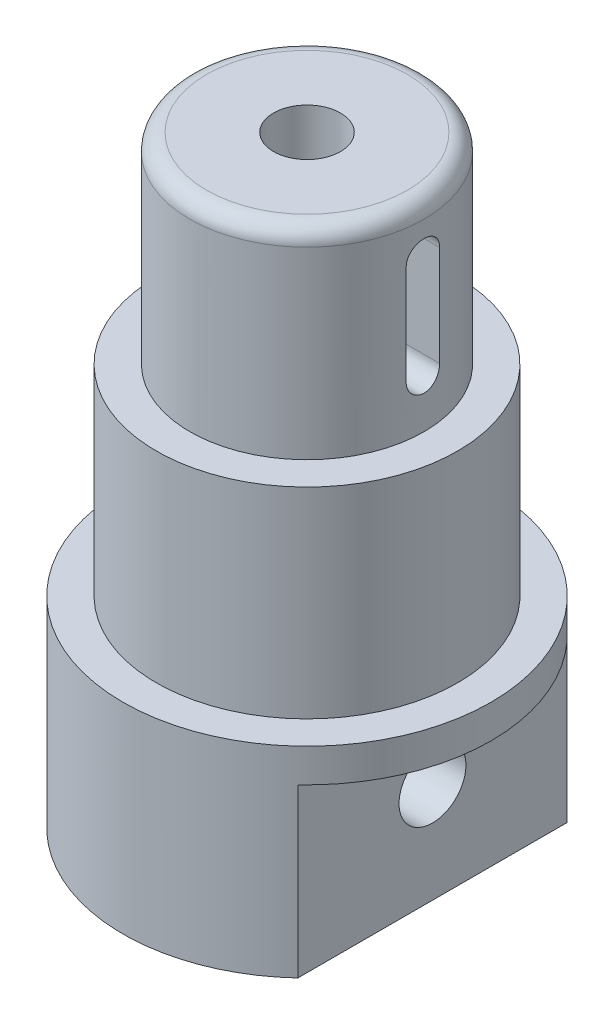
SolidWorks part; units mm, degrees
ref_plane "Front Plane" through (0, 0, 0) normal (0, 0, 1) x (1, 0, 0)
ref_plane "Top Plane" through (0, 0, 0) normal (0, 1, 0) x (1, 0, 0)
ref_plane "Right Plane" through (0, 0, 0) normal (1, 0, 0) x (0, 0, -1)
sketch "Sketch1" plane through (0, 0, 0) normal (0, 0, 1) x (1, 0, 0)
  line L0 (4, 0) -> (4, 72)
  line L1 (4, 72) -> (14, 72)
  line L2 (14, 72) -> (14, 48)
  line L3 (14, 48) -> (18, 48)
  line L4 (18, 48) -> (18, 24)
  line L5 (18, 24) -> (22, 24)
  line L6 (22, 24) -> (22, 0)
  line L7 (22, 0) -> (4, 0)
  line L8 (0, 0) -> (0, 89.4028) construction
  dimension "D1" = 4
  dimension "D2" = 24
  dimension "D3" = 24
  dimension "D4" = 24
  dimension "D5" = 10
  dimension "D6" = 4
  dimension "D7" = 4
revolve "Revolve1" add sketch "Sketch1" angle 360 about L8
sketch "Sketch2" plane through (0, 0, 0) normal (0, -1, 0) x (1, 0, 0)
  line L0 (15, 16.0935) -> (15, -16.0935)
  circle A0 centre (0, 0) radius 22 construction
  arc A1 (15, -16.0935) -> (15, 16.0935) centre (0, 0) ccw
  dimension "D1" = 15
extrude "Cut-Extrude1" cut sketch "Sketch2" against normal blind 20
sketch "Sketch3" plane through (0, 0, 0) normal (1, 0, 0) x (0, 0, -1)
  line L0 (0, 66) -> (0, 54) construction
  line L1 (2, 66) -> (2, 54)
  line L2 (-2, 66) -> (-2, 54)
  line L3 (14, 72) -> (-14, 72) construction
  arc A0 (2, 66) -> (-2, 66) centre (0, 66) ccw
  arc A1 (-2, 54) -> (2, 54) centre (0, 54) ccw
  point P3 (0, 60)
  dimension "D2" = 2
  dimension "D1" = 12
  dimension "D3" = 12
extrude "Cut-Extrude2" cut sketch "Sketch3" along normal blind 20 from offset 9
hole_wizard "Hole1" positions "Sketch4" profile "Sketch5" legacy end condition through all
sketch "Sketch4" plane through (15, 0, 0) normal (1, 0, 0) x (0, 0, -1)
  line L0 (-16.0935, 0) -> (16.0935, 0) construction
  point P0 (0, 12)
  point P5 (0, 0)
  dimension "D1" = 12
sketch "Sketch5" plane through (15, 12, 0) normal (0, 1, 0) x (0, 0, -1)
  line L0 (0, 0) -> (0, 37)
  line L1 (0, 37) -> (4, 37)
  line L2 (4, 37) -> (4, 0)
  line L3 (4, 0) -> (0, 0)
  line L4 (0, 110) -> (0, -10) construction
  dimension "Diameter" = 8
  dimension "Depth" = 37
mirror "Mirror2" about plane through (0, 0, 0) normal (1, 0, 0) of "Cut-Extrude2"
mirror "Mirror3" about plane through (0, 0, 0) normal (1, 0, 0) of "Cut-Extrude1"
fillet "Fillet1" radius 2 1 edges at (0, 72, -14)
